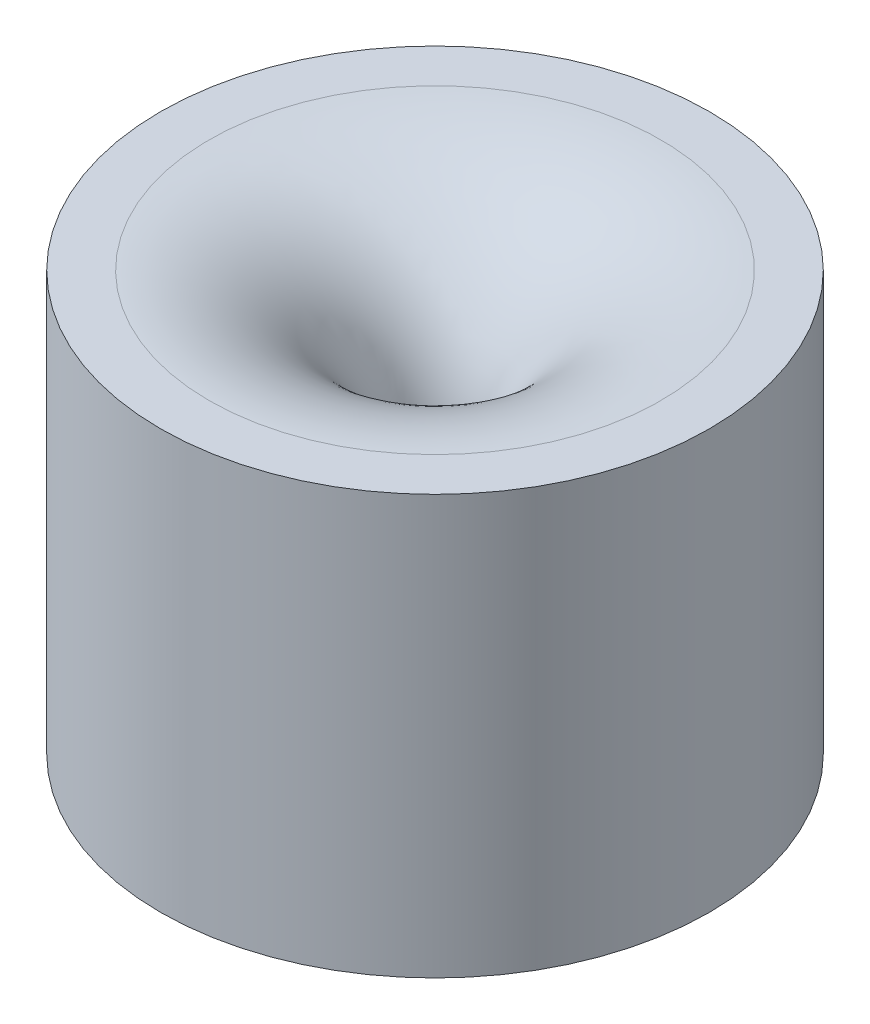
SolidWorks part; units mm, degrees
ref_plane "Front Plane" through (0, 0, 0) normal (0, 0, 1) x (1, 0, 0)
ref_plane "Top Plane" through (0, 0, 0) normal (0, 1, 0) x (1, 0, 0)
ref_plane "Right Plane" through (0, 0, 0) normal (1, 0, 0) x (0, 0, -1)
sketch "Sketch1" plane through (0, 0, 0) normal (0, 1, 0) x (1, 0, 0)
  circle A0 centre (0, 0) radius 4
  circle A1 centre (0, 0) radius 29.175
  dimension "D1" = 8
  dimension "D2" = 58.35
extrude "Boss-Extrude1" add sketch "Sketch1" along normal blind 44.5
fillet "Fillet1" radius 20 1 edges at (0, 44.5, 4)
